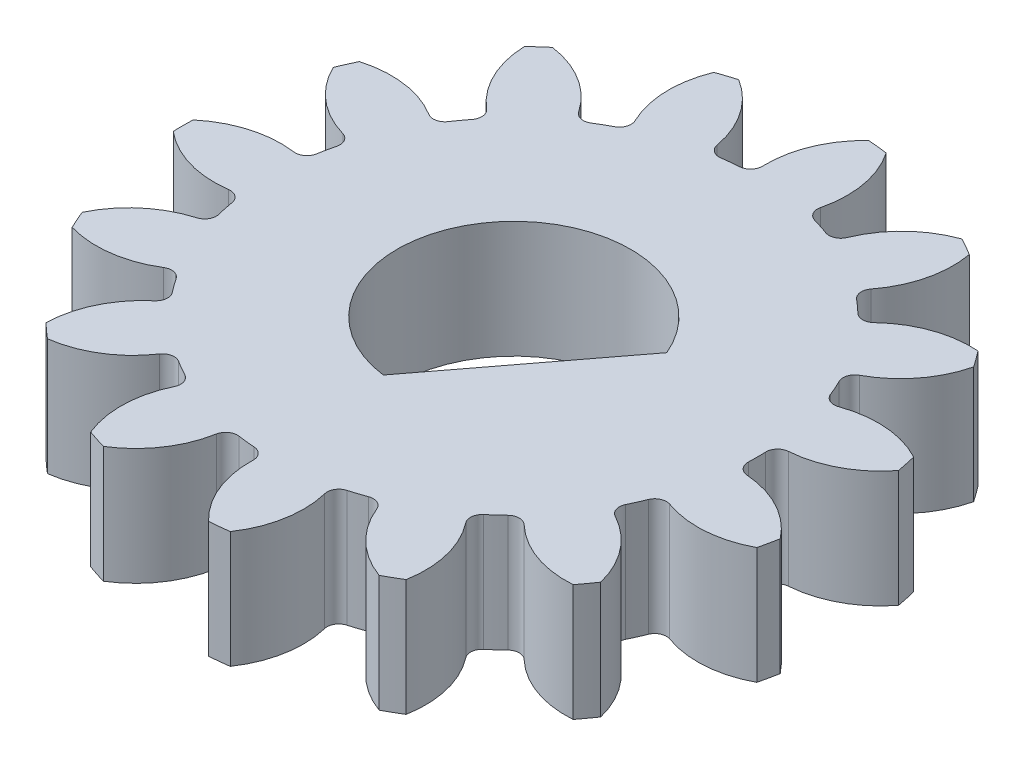
SolidWorks part; units mm, degrees
ref_plane "Alzado" through (0, 0, 0) normal (0, 0, 1) x (1, 0, 0)
ref_plane "Planta" through (0, 0, 0) normal (0, 1, 0) x (1, 0, 0)
ref_plane "Vista lateral" through (0, 0, 0) normal (1, 0, 0) x (0, 0, -1)
sketch "Croquis1" plane through (0, 0, 0) normal (0, 1, 0) x (1, 0, 0)
  line L0 (0, 0) -> (0, 18.2727) construction
  line L1 (0, 7.5) -> (2.4105, 6.6226) construction
  line L2 (0, 0) -> (1.9322, 18.3495) construction
  line L3 (1.5622, 7.3355) -> (-0.9782, 6.9795) construction
  circle A0 centre (0, 0) radius 7.0477 construction
  circle A1 centre (0, 0) radius 6.25 construction
  circle A2 centre (0, 0) radius 7.5 construction
  circle A3 centre (0, 0) radius 8.5 construction
  arc A4 (0.6371, 8.4761) -> (-0.1273, 6.2487) centre (2.4105, 6.6226) ccw
  arc A5 (1.1424, 8.4229) -> (1.426, 6.0851) centre (-0.9782, 6.9795) cw
  dimension "De" = 17
  dimension "Dp" = 15
  dimension "Di" = 12.5
  dimension "Ct" = 14.0953
  dimension "E" = 1.5708
sketch "Croquis3" plane through (0, 0, 0) normal (0, 1, 0) x (1, 0, 0)
  circle A0 centre (0, 0) radius 8.5 construction
  arc A1 (1.426, 6.0851) -> (1.1424, 8.4229) centre (-0.9782, 6.9795) ccw construction
  circle A2 centre (0, 0) radius 6.25 construction
  arc A3 (0.6371, 8.4761) -> (-0.1273, 6.2487) centre (2.4105, 6.6226) ccw construction
  arc A4 (1.1424, 8.4229) -> (0.6371, 8.4761) centre (0, 0) ccw
  arc A5 (1.426, 6.0851) -> (1.1424, 8.4229) centre (-0.9782, 6.9795) ccw
  arc A6 (-0.1273, 6.2487) -> (1.426, 6.0851) centre (0, 0) ccw
  arc A7 (0.6371, 8.4761) -> (-0.1273, 6.2487) centre (2.4105, 6.6226) ccw
extrude "Saliente-Extruir1" add sketch "Croquis3" along normal blind 3 contours A6 A5 A4 A7
fillet "Redondeo1" radius 0.3 2 edges at (-0.1273, 1.5, -6.2487) (1.426, 1.5, -6.0851)
pattern_circular "MatrizC1" count 15 over 360 about axis through (0, 0, 0) along (0, 1, 0) of "Saliente-Extruir1", "Redondeo1"
sketch "Croquis4" plane through (0, 0, 0) normal (0, -1, 0) x (1, 0, 0)
  circle A0 centre (0, 0) radius 6.25
sketch "Croquis5" plane through (0, 0, 0) normal (0, -1, 0) x (1, 0, 0)
  line L0 (2.766, -1.1615) -> (2.4042, -0.6853) construction
  line L1 (-0.0153, 2.5) -> (-0.3771, 2.9762) construction
  line L2 (-0.0153, 2.5) -> (2.4042, -0.6853) construction
  line L3 (2.766, -1.1615) -> (2.4042, -0.6853)
  line L4 (-0.0153, 2.5) -> (-0.3771, 2.9762)
  line L5 (-0.0153, 2.5) -> (2.4042, -0.6853)
  arc A0 (-0.3771, 2.9762) -> (2.766, -1.1615) centre (0, 0) ccw construction
  arc A1 (-0.3771, 2.9762) -> (2.766, -1.1615) centre (0, 0) ccw
extrude "Cortar-Extruir1" cut sketch "Croquis5" against normal blind 10
equation "\"M\"= 1"
equation "\"N\"= 15"
equation "\"a\"= 20"
equation "\"De@Croquis1\"= \"M\" * ( \"N\" + 2 )"
equation "\"Dp@Croquis1\"= \"M\" * \"N\""
equation "\"Di@Croquis1\" = \"Dp@Croquis1\" - \"M\" * 2.5"
equation "\"Ct@Croquis1\"= \"Dp@Croquis1\" * 0.93969"
equation "\"E@Croquis1\"= \"M\" * 1.5708"
equation "\"D1@Redondeo1\"=\"M\"*0.3"
equation "\"D1@MatrizC1\"=\"N\""
